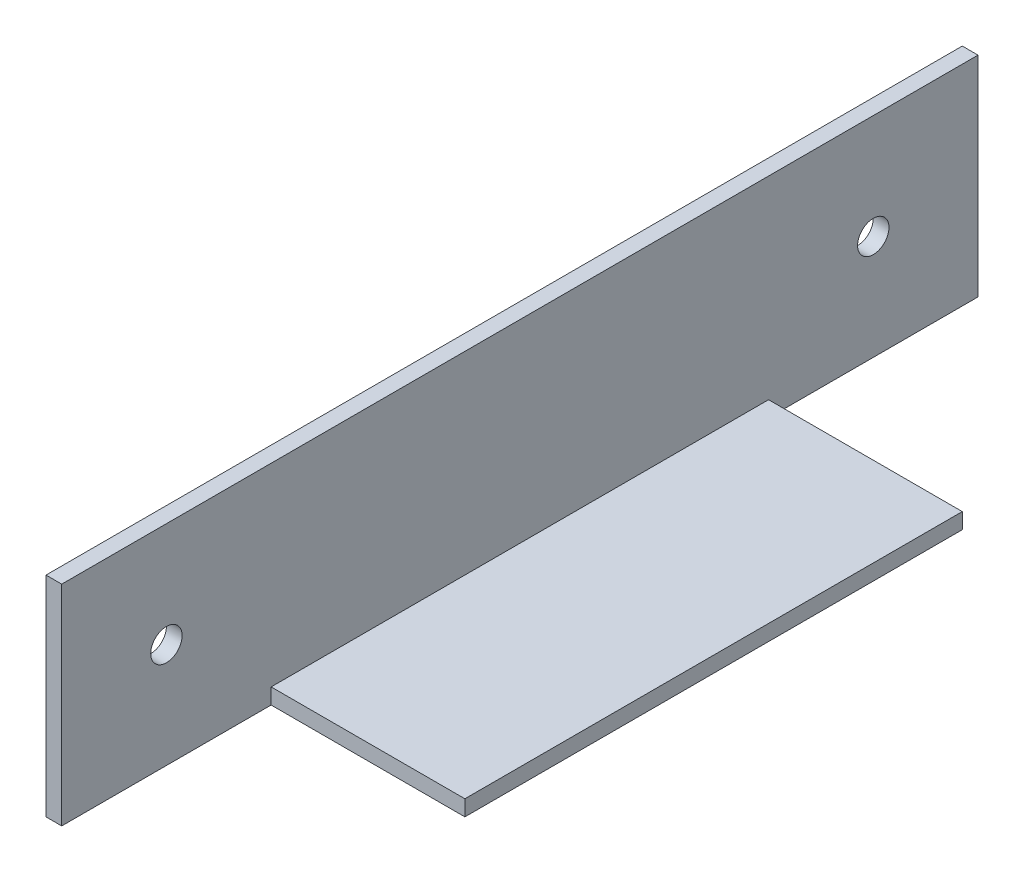
SolidWorks part; units mm, degrees
ref_plane "Plan de face" through (0, 0, 0) normal (0, 0, 1) x (1, 0, 0)
ref_plane "Plan de dessus" through (0, 0, 0) normal (0, 1, 0) x (1, 0, 0)
ref_plane "Plan de droite" through (0, 0, 0) normal (1, 0, 0) x (0, 0, -1)
sketch "Esquisse1" plane through (0, 0, 0) normal (0, 0, 1) x (1, 0, 0)
  line L0 (0, 0) -> (20, 0)
  line L1 (20, 0) -> (20, 1.5)
  line L2 (20, 1.5) -> (1.5, 1.5)
  line L3 (1.5, 1.5) -> (1.5, 20)
  line L4 (1.5, 20) -> (0, 20)
  line L5 (0, 20) -> (0, 0)
  dimension "D1" = 1.5
  dimension "D2" = 1.5
  dimension "D3" = 20
  dimension "D4" = 20
extrude "Extrusion1" add sketch "Esquisse1" along normal blind 87.5
sketch "Esquisse3" plane through (0, 0, 0) normal (-1, 0, 0) x (0, 0, 1)
  line L0 (77.5, 10) -> (13, 10) construction
  line L1 (87.5, 20) -> (87.5, 0) construction
  line L2 (0, 20) -> (0, 0) construction
  circle A0 centre (77.5, 10) radius 1.5
  circle A3 centre (10, 10) radius 1.5
  point P10 (0, 10)
  dimension "D1" = 10
  dimension "D2" = 10
extrude "Extrusion3" cut sketch "Esquisse3" against normal blind 10
sketch "Esquisse4" plane through (0, 0, 0) normal (0, -1, 0) x (1, 0, 0)
  line L1 (20, 0) -> (1.5, 0)
  line L2 (20, 0) -> (20, 20)
  line L3 (20, 20) -> (1.5, 20)
  line L4 (1.5, 0) -> (1.5, 20)
  line L5 (20, 87.5) -> (1.5, 87.5)
  line L6 (20, 87.5) -> (20, 67.5)
  line L7 (20, 67.5) -> (1.5, 67.5)
  line L8 (1.5, 87.5) -> (1.5, 67.5)
  dimension "D1" = 18.5
  dimension "D2" = 20
  dimension "D3" = 20
  dimension "D4" = 18.5
extrude "Extrusion4" cut sketch "Esquisse4" against normal blind 1.5
